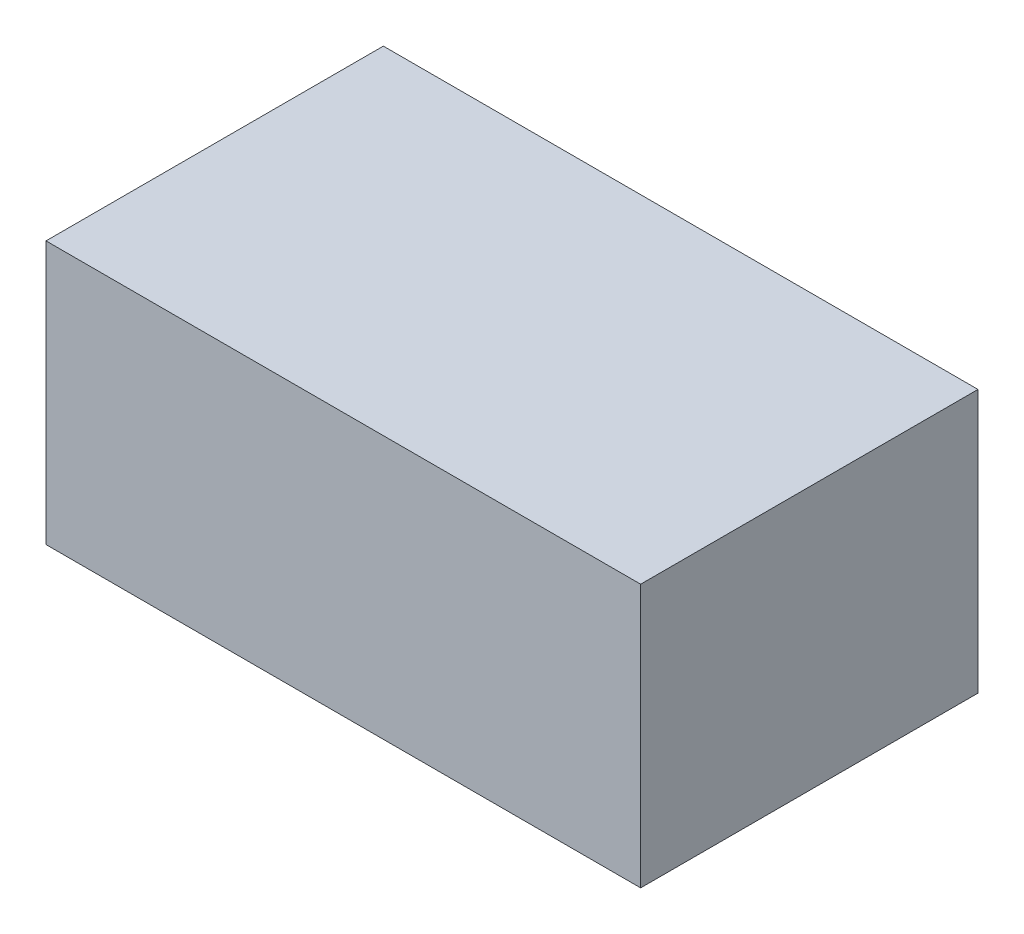
SolidWorks part; units mm, degrees
ref_plane "Front Plane" through (0, 0, 0) normal (0, 0, 1) x (1, 0, 0)
ref_plane "Top Plane" through (0, 0, 0) normal (0, 1, 0) x (1, 0, 0)
ref_plane "Right Plane" through (0, 0, 0) normal (1, 0, 0) x (0, 0, -1)
sketch "Sketch1" plane through (0, 0, 0) normal (0, 1, 0) x (1, 0, 0)
  line L1 (0, 0) -> (104, 0)
  line L2 (0, 0) -> (0, 59)
  line L3 (0, 59) -> (104, 59)
  line L4 (104, 0) -> (104, 59)
  dimension "D1" = 59
  dimension "D2" = 104
extrude "Boss-Extrude1" add sketch "Sketch1" along normal blind 46
